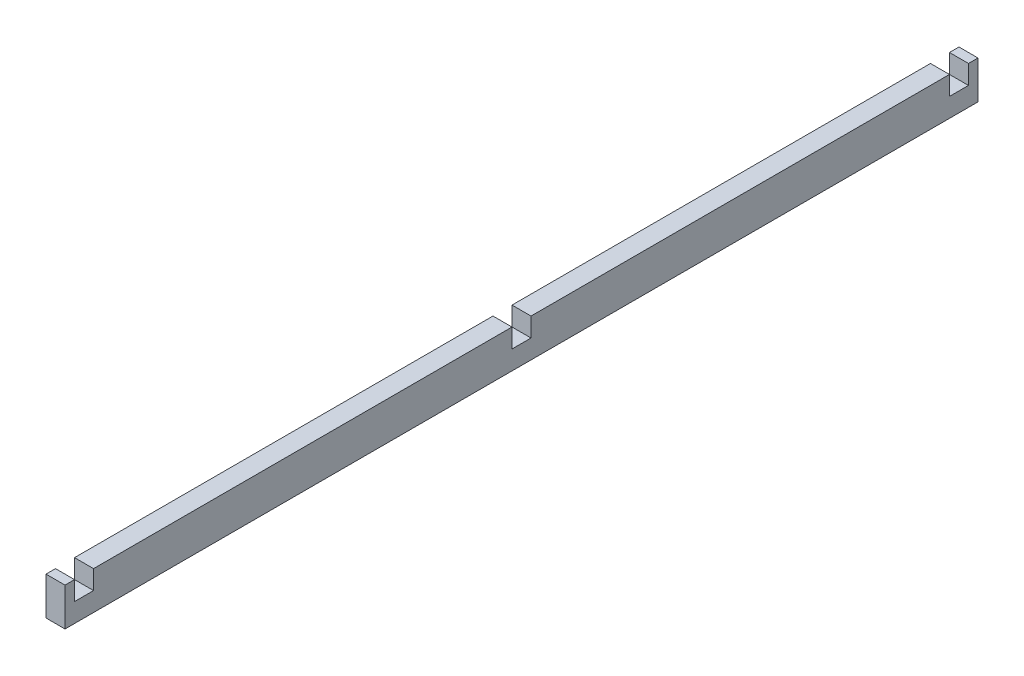
SolidWorks part; units mm, degrees
ref_plane "Front Plane" through (0, 0, 0) normal (0, 0, 1) x (1, 0, 0)
ref_plane "Top Plane" through (0, 0, 0) normal (0, 1, 0) x (1, 0, 0)
ref_plane "Right Plane" through (0, 0, 0) normal (1, 0, 0) x (0, 0, -1)
sketch "Sketch1" plane through (0, 0, 0) normal (0, 0, 1) x (1, 0, 0)
  line L1 (-25.4, -50.8) -> (25.4, -50.8)
  line L2 (-25.4, -50.8) -> (-25.4, 50.8)
  line L3 (-25.4, 50.8) -> (25.4, 50.8)
  line L4 (25.4, -50.8) -> (25.4, 50.8)
  line L5 (-25.4, -50.8) -> (25.4, 50.8) construction
  line L6 (-25.4, 50.8) -> (25.4, -50.8) construction
  point P0 (0, 0)
  dimension "D1" = 101.6
  dimension "D2" = 50.8
extrude "Boss-Extrude1" add sketch "Sketch1" along normal blind 2438.4
sketch "Sketch2" plane through (25.4, 0, 0) normal (1, 0, 0) x (0, 0, -1)
  line L0 (-2438.4, 50.8) -> (0, 50.8) construction
  line L1 (-1244.6, 50.8) -> (-1244.6, 0)
  line L2 (-2413, 50.8) -> (-2362.2, 50.8)
  line L3 (-2413, 50.8) -> (-2413, 0)
  line L4 (-2413, 0) -> (-2362.2, 0)
  line L5 (-2362.2, 50.8) -> (-2362.2, 0)
  line L6 (-1244.6, 50.8) -> (-1193.8, 50.8)
  line L7 (-1193.8, 50.8) -> (-1193.8, 0)
  line L8 (-1244.6, 0) -> (-1193.8, 0)
  line L9 (-76.2, 50.8) -> (-76.2, 0)
  line L10 (-76.2, 50.8) -> (-25.4, 50.8)
  line L11 (-25.4, 50.8) -> (-25.4, 0)
  line L12 (-76.2, 0) -> (-25.4, 0)
  dimension "D1" = 25.4
  dimension "D2" = 50.8
  dimension "D3" = 50.8
  dimension "D4" = 3
extrude "Cut-Extrude1" cut sketch "Sketch2" against normal through all both and the other way through all
